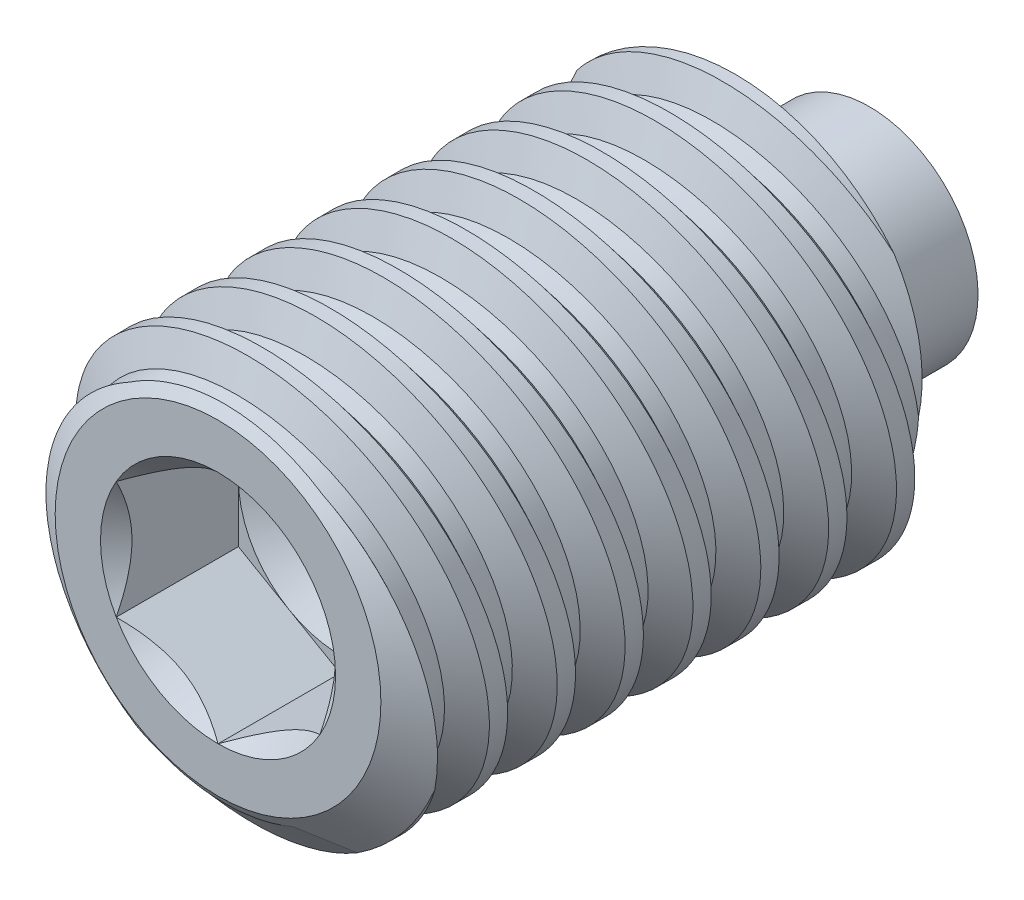
SolidWorks part; units mm, degrees
material "Purchase"
ref_plane "Front" through (0, 0, 0) normal (0, 0, 1) x (1, 0, 0)
ref_plane "Top" through (0, 0, 0) normal (0, 1, 0) x (1, 0, 0)
ref_plane "Right" through (0, 0, 0) normal (1, 0, 0) x (0, 0, -1)
sketch "Sketch22" plane through (0, 0, 0) normal (1, 0, 0) x (0, 0, -1)
  line L0 (-2.4, 0) -> (-2.4, 1.2)
  line L1 (-2.4, 1.2) -> (-2.1899, 1.5)
  line L2 (-2.1899, 1.5) -> (1.4124, 1.5)
  line L3 (1.4124, 1.5) -> (1.6, 0.8)
  line L5 (2.4, 0) -> (-2.4, 0)
  line L6 (2.4, 0) -> (3.4, 0) construction
  line L7 (2.4, 0) -> (2.4, 0.8)
  line L8 (2.4, 0.8) -> (1.6, 0.8)
  line L9 (-2.1899, -1.5) -> (1.4124, -1.5) construction
  dimension "D1" = 1
  dimension "Screw Dia" = 3
  dimension "D2" = 105
  dimension "Length" = 4
  dimension "D3" = 35
  dimension "D4" = 3.8124
  dimension "D7" = 2.4
  dimension "Tip Diameter" = 1.6
  dimension "Tip Length" = 0.8
revolve "Revolve1" add sketch "Sketch22" angle 360 about L6
sketch "Sketch6" plane through (0, 0, 0) normal (1, 0, 0) x (0, 0, -1)
  line L0 (0.8576, 1.5) -> (1.3576, -1.5) construction
  line L1 (-2.1899, 1.5) -> (1.4124, 1.5) construction
  line L2 (-2.1899, -1.5) -> (1.4124, -1.5) construction
  line L3 (0.8576, 1.5) -> (0.9192, 1.5103) construction
  line L4 (1.2412, 1.2896) -> (1.1179, 1.269)
  line L5 (1.1179, 1.269) -> (0.9192, 1.5103)
  line L6 (1.2412, 1.2896) -> (1.3508, 1.5822)
  line L7 (1.3508, 1.5822) -> (0.9192, 1.5103)
  line L8 (1.1427, 1.5) -> (1.6427, -1.5) construction
  line L9 (1.9278, 0.0892) -> (0.8576, -0.0892) construction
  line L10 (1.135, 1.5462) -> (1.1795, 1.2793) construction
  line L12 (1.3508, 1.5) -> (1.4124, 1.5103) construction
  line L13 (0.8576, -1.5) -> (0.8576, 1.5) construction
  line L14 (0.8576, -1.5) -> (1.3576, -1.5) construction
  line L15 (1.3576, -1.5) -> (1.6427, -1.5) construction
  line L16 (1.3508, 1.5822) -> (1.3508, 1.5) construction
  line L17 (1.4124, 1.5103) -> (1.4124, 1.5) construction
  line L18 (0.8576, 1.5) -> (1.1427, 1.5) construction
  point P18 (1.3927, 0)
  dimension "D1" = 0.5
  dimension "D2" = 0.125
  dimension "D3" = 60
  dimension "D4" = 0.0625
  dimension "Pitch" = 0.5
revolve "Cut-Revolve8" cut sketch "Sketch6" angle 360 about L9
pattern_linear "LPattern1" count 9 spacing 0.5 along (0, 0, 1) count 2 spacing 0.5 along (0, 0, 1) of "Cut-Revolve8"
sketch "Sketch23" plane through (0, 0, 2.4) normal (0, 0, 1) x (1, 0, 0)
  line L1 (0, 0.866) -> (-0.75, 0.433)
  line L2 (-0.75, 0.433) -> (-0.75, -0.433)
  line L3 (-0.75, -0.433) -> (0, -0.866)
  line L4 (0, -0.866) -> (0.75, -0.433)
  line L5 (0.75, -0.433) -> (0.75, 0.433)
  line L6 (0.75, 0.433) -> (0, 0.866)
  circle A0 centre (0, 0) radius 0.75 construction
  dimension "Hex" = 1.5
extrude "Cut-Extrude10" cut sketch "Sketch23" against normal blind 0.9
sketch "Sketch24" plane through (0, 0, 2.4) normal (0, 0, 1) x (1, 0, 0)
  circle A0 centre (0, 0) radius 0.866
extrude "Cut-Extrude11" cut sketch "Sketch24" against normal through all draft 45
sketch "Sketch26" plane through (0, 0, 1.5) normal (0, 0, 1) x (1, 0, 0)
  circle A0 centre (0, 0) radius 0.75 construction
  circle A1 centre (0, 0) radius 0.75
extrude "Cut-Extrude12" cut sketch "Sketch26" against normal through all draft 59
equation "\"D2@Sketch6\"=\"Pitch@Sketch6\"/4"
equation "\"D4@Sketch6\"=\"Pitch@Sketch6\"/8"
equation "\"D1@Sketch6\"=\"Pitch@Sketch6\""
equation "\"D3@LPattern1\"=\"Pitch@Sketch6\""
equation "\"D1@LPattern1\"=(\"D4@Sketch22\"/\"Pitch@Sketch6\")+1"
equation "\"D4@LPattern1\"=\"Pitch@Sketch6\""
equation "\"D7@Sketch22\"=\"Screw Dia@Sketch22\"*.8"
